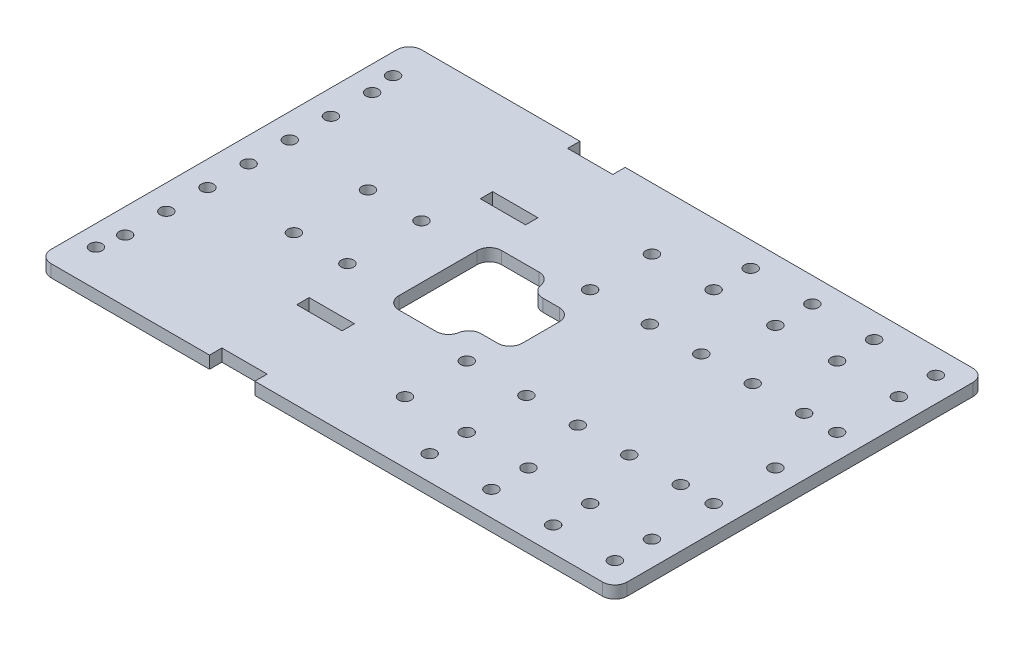
SolidWorks part; units mm, degrees
ref_plane "Front Plane" through (0, 0, 0) normal (0, 0, 1) x (1, 0, 0)
ref_plane "Top Plane" through (0, 0, 0) normal (0, 1, 0) x (1, 0, 0)
ref_plane "Right Plane" through (0, 0, 0) normal (1, 0, 0) x (0, 0, -1)
sketch "Sketch1" plane through (0, 0, 0) normal (0, 1, 0) x (1, 0, 0)
  line L1 (0, 0) -> (140, 0)
  line L2 (0, 0) -> (0, 90)
  line L3 (0, 90) -> (140, 90)
  line L4 (140, 0) -> (140, 90)
  dimension "D1" = 90
  dimension "D2" = 140
extrude "Plain Board" add sketch "Sketch1" along normal blind 3
sketch "Sketch2" plane through (0, 3, 0) normal (0, 1, 0) x (1, 0, 0)
  line L0 (0, 0) -> (140, 0) construction
  line L1 (41.5, 0) -> (52.5, 0)
  line L2 (41.5, 0) -> (41.5, 3)
  line L3 (41.5, 3) -> (52.5, 3)
  line L4 (52.5, 0) -> (52.5, 3)
  line L5 (0, 45) -> (39.6449, 45) construction
  line L6 (41.5, 21.2) -> (52.5, 21.2)
  line L7 (41.5, 21.2) -> (41.5, 24.2)
  line L8 (41.5, 24.2) -> (52.5, 24.2)
  line L9 (52.5, 21.2) -> (52.5, 24.2)
  line L10 (0, 90) -> (0, 0) construction
  line L11 (52.5, 68.8) -> (52.5, 65.8)
  line L12 (41.5, 65.8) -> (52.5, 65.8)
  line L13 (41.5, 68.8) -> (41.5, 65.8)
  line L14 (41.5, 68.8) -> (52.5, 68.8)
  line L15 (52.5, 90) -> (52.5, 87)
  line L16 (41.5, 87) -> (52.5, 87)
  line L17 (41.5, 90) -> (41.5, 87)
  line L18 (41.5, 90) -> (52.5, 90)
  dimension "D1" = 3
  dimension "D2" = 11
  dimension "D3" = 3
  dimension "D4" = 11
  dimension "D5" = 41.5
  dimension "D6" = 41.5
  dimension "D7" = 21.2
extrude "Motor Mount" cut sketch "Sketch2" against normal blind 3
sketch "Sketch3" plane through (0, 3, 0) normal (0, 1, 0) x (1, 0, 0)
  line L0 (140, 0) -> (140, 90) construction
  line L1 (140, 90) -> (52.5, 90) construction
  circle A0 centre (126, 60) radius 1.5
  circle A1 centre (113.5, 60) radius 1.5
  circle A2 centre (101, 60) radius 1.5
  circle A3 centre (88.5, 60) radius 1.5
  circle A4 centre (113.5, 30) radius 1.5
  circle A5 centre (101, 30) radius 1.5
  circle A6 centre (88.5, 30) radius 1.5
  circle A7 centre (126, 30) radius 1.5
  dimension "D1" = 3
  dimension "D2" = 14
  dimension "D3" = 30
  dimension "D4" = 4
  dimension "D5" = 2
extrude "Caster" cut sketch "Sketch3" against normal blind 3
sketch "Sketch4" plane through (0, 3, 0) normal (0, 1, 0) x (1, 0, 0)
  line L0 (0, 90) -> (0, 0) construction
  line L1 (0, 0) -> (41.5, 0) construction
  line L2 (0, 45) -> (23.6505, 45) construction
  circle A0 centre (5, 8.9) radius 1.5
  circle A1 centre (26, 36) radius 1.5
  circle A2 centre (39, 36) radius 1.5
  circle A3 centre (5, 81.1) radius 1.5
  circle A4 centre (39, 54) radius 1.5
  circle A5 centre (26, 54) radius 1.5
  dimension "D1" = 5
  dimension "D2" = 8.9
  dimension "D3" = 3
  dimension "D4" = 3
  dimension "D5" = 3
  dimension "D6" = 26
  dimension "D7" = 13
  dimension "D8" = 9
extrude "PCBs" cut sketch "Sketch4" against normal blind 3
sketch "Sketch5" plane through (0, 3, 0) normal (0, 1, 0) x (1, 0, 0)
  line L0 (0, 90) -> (0, 0) construction
  line L1 (52, 57.5) -> (67, 57.5)
  line L2 (52, 57.5) -> (52, 32.5)
  line L3 (52, 32.5) -> (67, 32.5)
  line L4 (67, 57.5) -> (67, 32.5)
  line L5 (67, 52.5) -> (77, 52.5)
  line L6 (67, 52.5) -> (67, 37.5)
  line L7 (67, 37.5) -> (77, 37.5)
  line L8 (77, 52.5) -> (77, 37.5)
  point P10 (0, 45)
  dimension "D1" = 52
  dimension "D2" = 15
  dimension "D3" = 10
  dimension "D4" = 25
  dimension "D5" = 15
  dimension "D6" = 5
  dimension "D7" = 12.5
extrude "Cable Hole" cut sketch "Sketch5" against normal blind 3 contours L8 L5 L4 L7 | L4 L1 L2 L3
sketch "Sketch6" plane through (0, 3, 0) normal (0, 1, 0) x (1, 0, 0)
  line L0 (140, 0) -> (140, 90) construction
  circle A0 centre (134, 15) radius 1.5
  circle A1 centre (119, 15) radius 1.5
  circle A2 centre (104, 15) radius 1.5
  circle A3 centre (89, 15) radius 1.5
  circle A4 centre (119, 75) radius 1.5
  circle A5 centre (104, 75) radius 1.5
  circle A6 centre (89, 75) radius 1.5
  circle A7 centre (134, 75) radius 1.5
  point P4 (140, 45)
  dimension "D1" = 3
  dimension "D2" = 6
  dimension "D3" = 30
  dimension "D4" = 4
  dimension "D5" = 2
extrude "Servo Board " cut sketch "Sketch6" against normal blind 3
sketch "Sketch7" plane through (0, 3, 0) normal (0, 1, 0) x (1, 0, 0)
  line L0 (140, 0) -> (140, 90) construction
  line L1 (52.5, 0) -> (140, 0) construction
  line L2 (0, 90) -> (0, 0) construction
  line L3 (0, 0) -> (41.5, 0) construction
  line L4 (140, 45) -> (36.4982, 45) construction
  circle A0 centre (134, 45) radius 1.5
  circle A1 centre (134, 6) radius 1.5
  circle A2 centre (119, 6) radius 1.5
  circle A3 centre (104, 6) radius 1.5
  circle A4 centre (89, 6) radius 1.5
  circle A5 centre (134, 60) radius 1.5
  circle A6 centre (134, 30) radius 1.5
  circle A7 centre (6, 45) radius 1.5
  circle A8 centre (6, 35) radius 1.5
  circle A9 centre (6, 25) radius 1.5
  circle A10 centre (6, 15) radius 1.5
  circle A13 centre (89, 84) radius 1.5
  circle A14 centre (104, 84) radius 1.5
  circle A15 centre (119, 84) radius 1.5
  circle A16 centre (134, 84) radius 1.5
  circle A17 centre (6, 75) radius 1.5
  circle A18 centre (6, 65) radius 1.5
  circle A19 centre (6, 55) radius 1.5
  point P2 (140, 45)
  dimension "D1" = 3
  dimension "D2" = 6
  dimension "D3" = 3
  dimension "D4" = 6
  dimension "D5" = 6
  dimension "D6" = 45
  dimension "D9" = 6
  dimension "D10" = 45
  dimension "D11" = 3
  dimension "D13" = 3
  dimension "D8" = 6
  dimension "D14" = 15
  dimension "D7" = 4
  dimension "D12" = 4
extrude "Sensor Holes" cut sketch "Sketch7" against normal blind 3
sketch "Sketch8" plane through (0, 3, 0) normal (0, 1, 0) x (1, 0, 0)
  line L0 (140, 0) -> (140, 90) construction
  line L1 (0, 45) -> (21.3194, 45) construction
  line L2 (0, 90) -> (0, 0) construction
  circle A0 centre (74, 60) radius 1.5
  circle A2 centre (134, 60) radius 1.5 construction
  circle A3 centre (74, 75) radius 1.5
  circle A4 centre (74, 15) radius 1.5
  circle A5 centre (74, 30) radius 1.5
  point P4 (140, 45)
  point P7 (140, 45)
  dimension "D1" = 60
  dimension "D2" = 3
  dimension "D3" = 15
  dimension "D4" = 2
extrude "Servo Board(2)" cut sketch "Sketch8" against normal blind 3
fillet "Fillet1" radius 3 7 edges at (0, 1.5, -90) (52, 1.5, -32.5) (52, 1.5, -57.5) (77, 1.5, -37.5) (67, 1.5, -37.5) (77, 1.5, -52.5) (67, 1.5, -52.5)
fillet "Fillet3" radius 3 5 edges at (140, 1.5, -90) (140, 1.5, 0) (0, 1.5, 0) (67, 1.5, -57.5) (67, 1.5, -32.5)
